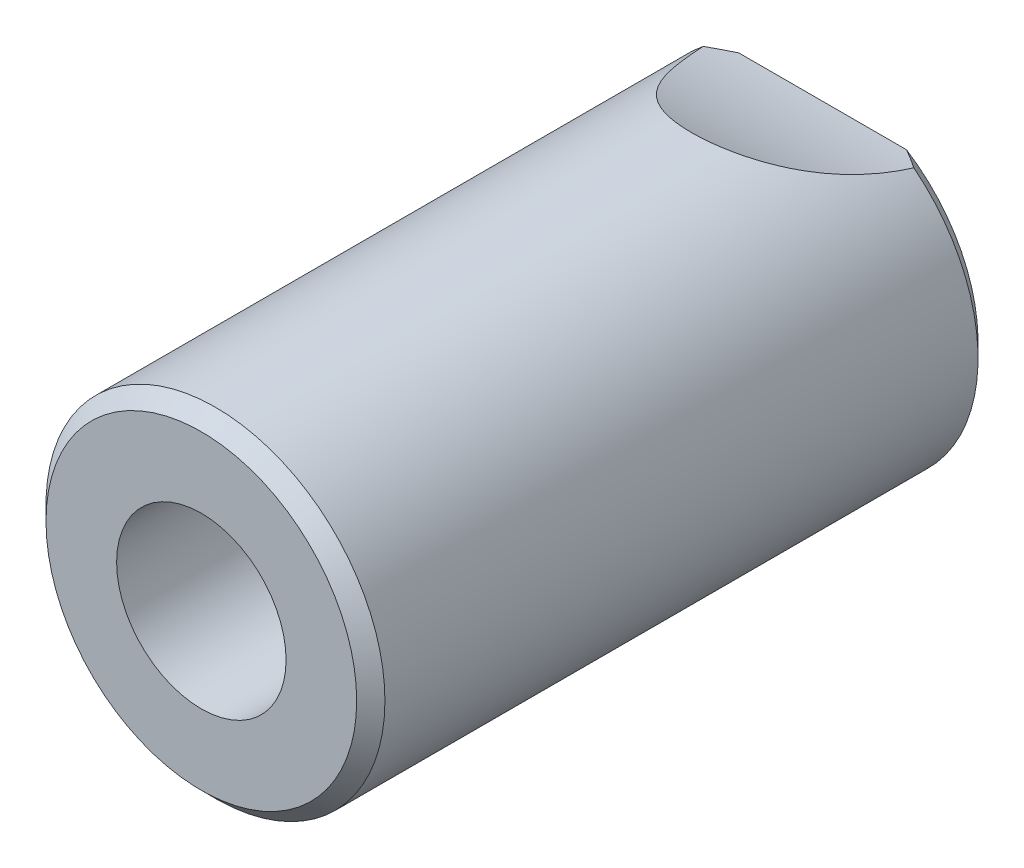
SolidWorks part; units mm, degrees
ref_plane "前视基准面" through (0, 0, 0) normal (0, 0, 1) x (1, 0, 0)
ref_plane "上视基准面" through (0, 0, 0) normal (0, 1, 0) x (1, 0, 0)
ref_plane "右视基准面" through (0, 0, 0) normal (1, 0, 0) x (0, 0, -1)
sketch "草图1" plane through (0, 0, 0) normal (0, 0, 1) x (1, 0, 0)
  circle A0 centre (0, 0) radius 12
  dimension "D1" = 24
extrude "凸台-拉伸1" add sketch "草图1" along normal blind 44
sketch "草图2" plane through (0, 0, 44) normal (0, 0, 1) x (1, 0, 0)
  circle A0 centre (0, 0) radius 6
  dimension "D1" = 12
extrude "切除-拉伸1" cut sketch "草图2" against normal through all both and the other way through all
chamfer "倒角1" distance 1 angle 45 2 edges at (12, 0, 0) (12, 0, 44)
sketch "草图3" plane through (0, 0, 0) normal (1, 0, 0) x (0, 0, -1)
  line L0 (0, -11) -> (0, 11) construction
  arc A0 (-25.1205, 29.3699) -> (1.5666, 9.0957) centre (4, 40) ccw
  dimension "D1" = 31
  dimension "D2" = 4
  dimension "D3" = 40
extrude "切除-拉伸2" cut sketch "草图3" against normal through all both and the other way through all
